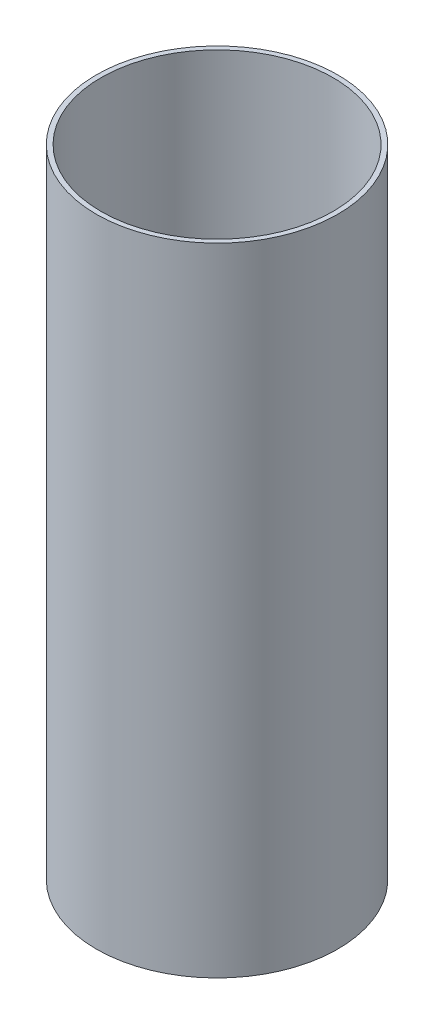
SolidWorks part; units mm, degrees
ref_plane "Front Plane" through (0, 0, 0) normal (0, 0, 1) x (1, 0, 0)
ref_plane "Top Plane" through (0, 0, 0) normal (0, 1, 0) x (1, 0, 0)
ref_plane "Right Plane" through (0, 0, 0) normal (1, 0, 0) x (0, 0, -1)
sketch "Sketch1" plane through (0, 0, 0) normal (0, 1, 0) x (1, 0, 0)
  circle A0 centre (0, 0) radius 36.45
  circle A1 centre (0, 0) radius 37.95
  dimension "D1" = 72.9
  dimension "D2" = 1.5
extrude "Boss-Extrude1" add sketch "Sketch1" along normal blind 200
